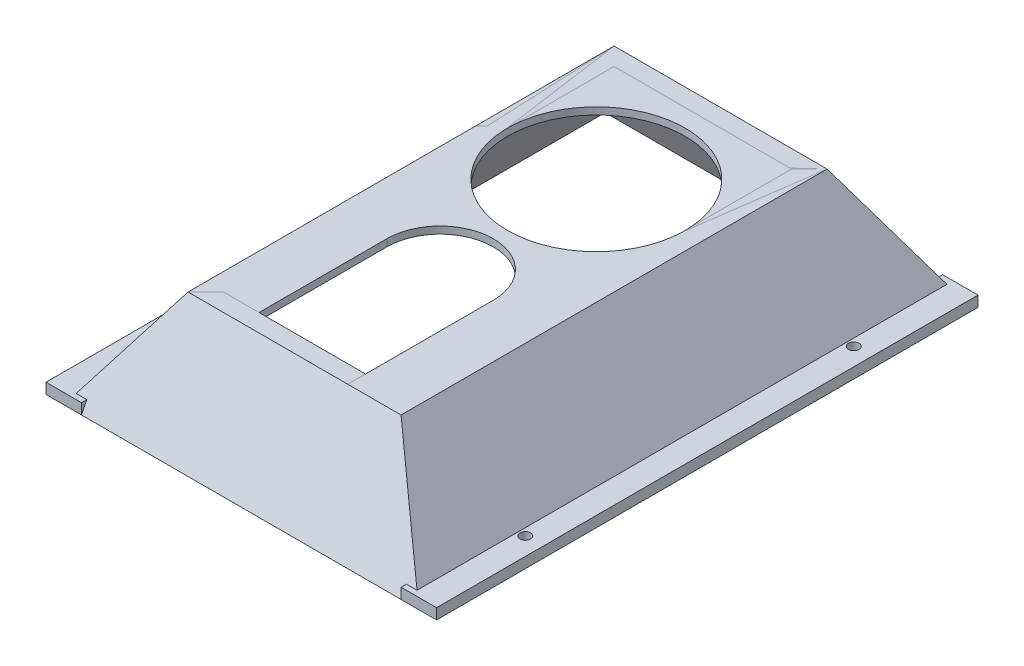
SolidWorks part; units mm, degrees
ref_plane "Front Plane" through (0, 0, 0) normal (0, 0, 1) x (1, 0, 0)
ref_plane "Top Plane" through (0, 0, 0) normal (0, 1, 0) x (1, 0, 0)
ref_plane "Right Plane" through (0, 0, 0) normal (1, 0, 0) x (0, 0, -1)
sketch "Sketch1" plane through (0, 0, 0) normal (0, 1, 0) x (1, 0, 0)
  line L20 (-50, 152.5) -> (50, 152.5)
  line L21 (-50, 152.5) -> (-50, 0)
  line L22 (-50, 0) -> (50, 0)
  line L23 (50, 152.5) -> (50, 0)
  point P4 (0, 0)
  dimension "D1" = 152.5
  dimension "D2" = 100
ref_plane "Plane1" through (0, 30, 0) normal (0, 1, 0) x (1, 0, 0)
sketch "Sketch3" plane through (0, 30, 0) normal (0, 1, 0) x (1, 0, 0)
  line L1 (-30, 135) -> (30, 135)
  line L2 (-30, 135) -> (-30, 15)
  line L3 (-30, 15) -> (30, 15)
  line L4 (30, 135) -> (30, 15)
  point P4 (0, 15)
  dimension "D1" = 120
  dimension "D2" = 60
  dimension "D3" = 15
loft "Loft8" add profiles "Sketch1", "Sketch3"
sketch "Sketch4" plane through (0, 30, 0) normal (0, 1, 0) x (1, 0, 0)
  line L0 (30, 135) -> (-30, 135) construction
  line L1 (-25, 130) -> (25, 130)
  line L2 (-25, 130) -> (-25, 20)
  line L3 (-25, 20) -> (25, 20)
  line L4 (25, 130) -> (25, 20)
  line L5 (-30, 15) -> (30, 15) construction
  line L6 (-30, 135) -> (-30, 15) construction
  point P8 (0, 20)
  dimension "D1" = 5
  dimension "D2" = 5
  dimension "D3" = 5
sketch "Sketch5" plane through (0, 0, 0) normal (0, 1, 0) x (1, 0, 0)
  line L0 (-50, 0) -> (50, 0) construction
  line L1 (-45, 147.5) -> (45, 147.5)
  line L2 (-45, 147.5) -> (-45, 5)
  line L3 (-45, 5) -> (45, 5)
  line L4 (45, 147.5) -> (45, 5)
  line L5 (-50, 152.5) -> (50, 152.5) construction
  line L6 (50, 152.5) -> (50, 0) construction
  point P10 (0, 5)
  dimension "D1" = 5
  dimension "D2" = 5
  dimension "D3" = 5
loft "Cut-Loft1" cut profiles "Sketch4", "Sketch5"
sketch "Sketch6" plane through (0, 0, 0) normal (0, 1, 0) x (1, 0, 0)
  line L14 (-45, 152.5) -> (-55, 152.5)
  line L15 (-50, 152.5) -> (50, 152.5) construction
  line L16 (-55, 152.5) -> (-55, 0)
  line L17 (-55, 0) -> (-45, 0)
  line L18 (-50, 0) -> (50, 0) construction
  line L19 (-45, 0) -> (-45, 152.5)
  line L20 (0, 150) -> (0, 0) construction
  line L21 (55, 0) -> (45, 0)
  line L22 (55, 152.5) -> (55, 0)
  line L23 (45, 152.5) -> (55, 152.5)
  line L24 (45, 0) -> (45, 152.5)
  line L25 (-50, 0) -> (-50, 30)
  line L26 (-50, 152.5) -> (-50, 122.5)
  point P10 (-50, 30)
  point P11 (-50, 122.5)
  point P13 (0, 0)
  point P26 (50, 30)
  point P27 (50, 122.5)
  dimension "D1" = 10
  dimension "D2" = 152.5
  dimension "D3" = 45
  dimension "D5" = 30
extrude "Boss-Extrude2" add sketch "Sketch6" along normal blind 3
hole_wizard "Ø3.0mm Dowel Hole1" positions "Sketch9" profile "Sketch10" hole size "Ø3.0" standard "ANSI Metric" end condition through all
sketch "Sketch9" plane through (0, 3, 0) normal (0, 1, 0) x (1, 0, 0)
  point P0 (50, 30)
  point P3 (-50, 30)
  point P6 (-50, 122.5)
  point P9 (50, 122.5)
sketch "Sketch10" plane through (50, 3, -30) normal (1, 0, 0) x (0, 0, 1)
  line L0 (0, 0) -> (0, 3.0001)
  line L1 (0, 3.0001) -> (1.5, 3.0001)
  line L2 (1.5, 3.0001) -> (1.5, 0)
  line L5 (1.5, 0) -> (0, 0)
  line L11 (0, -6.35) -> (0, 107.95) construction
  dimension "Thru Hole Dia." = 3
  dimension "Thru Hole Depth" = 3.0001
sketch "Sketch12" plane through (0, 30, 0) normal (0, 1, 0) x (1, 0, 0)
  line L0 (-15, 56) -> (-15, 15)
  line L2 (0, 1) -> (0, 63.6102) construction
  line L7 (15, 56) -> (15, 15)
  line L12 (-30, 135) -> (30, 135)
  line L13 (-30, 135) -> (-30, 15)
  line L14 (-30, 15) -> (30, 15)
  line L15 (30, 135) -> (30, 15)
  arc A0 (-15, 56) -> (15, 56) centre (0, 56) cw
  circle A2 centre (0, 100) radius 25
  point P16 (0, 71)
  dimension "D3" = 15
  dimension "D5" = 29
  dimension "D6" = 50
  dimension "D1" = 15
  dimension "D2" = 41
extrude "Boss-Extrude3" add sketch "Sketch12" against normal blind 2 separate body
